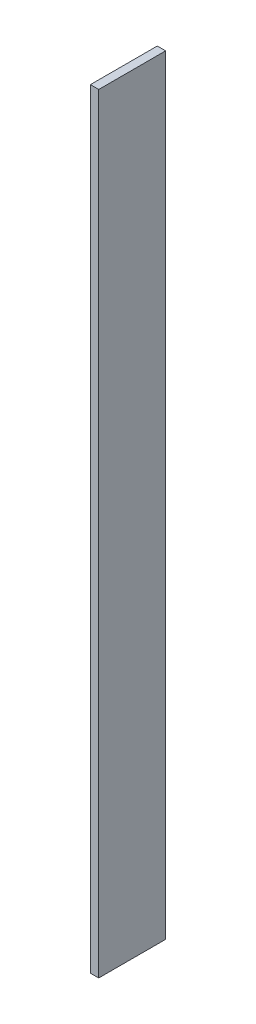
SolidWorks part; units mm, degrees
material "Zoltek Panex 33"
ref_plane "Front Plane" through (0, 0, 0) normal (0, 0, 1) x (1, 0, 0)
ref_plane "Top Plane" through (0, 0, 0) normal (0, 1, 0) x (1, 0, 0)
ref_plane "Right Plane" through (0, 0, 0) normal (1, 0, 0) x (0, 0, -1)
sketch "Sketch1" plane through (0, 0, 0) normal (0, 1, 0) x (1, 0, 0)
  line L1 (0.25, -2) -> (-0.25, -2)
  line L2 (0.25, -2) -> (0.25, 2)
  line L3 (0.25, 2) -> (-0.25, 2)
  line L4 (-0.25, -2) -> (-0.25, 2)
  line L5 (0.25, -2) -> (-0.25, 2) construction
  line L6 (0.25, 2) -> (-0.25, -2) construction
  point P0 (0, 0)
  dimension "D1" = 0.5
  dimension "D2" = 4
extrude "Boss-Extrude1" add sketch "Sketch1" along normal mid plane 46
